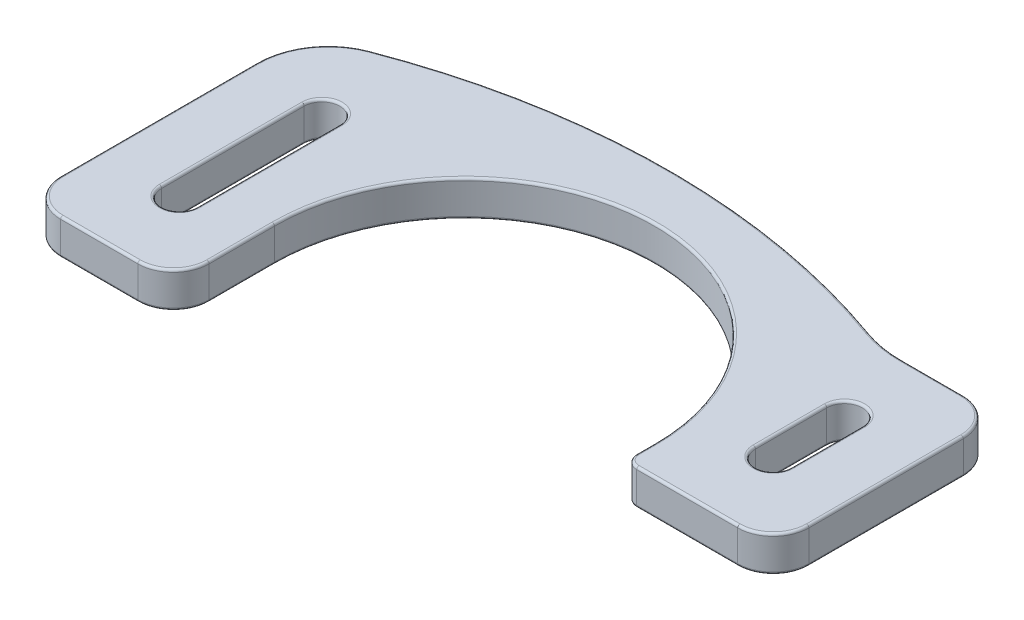
SolidWorks part; units mm, degrees
ref_plane "Front Plane" through (0, 0, 0) normal (0, 0, 1) x (1, 0, 0)
ref_plane "Top Plane" through (0, 0, 0) normal (0, 1, 0) x (1, 0, 0)
ref_plane "Right Plane" through (0, 0, 0) normal (1, 0, 0) x (0, 0, -1)
sketch "Sketch1" plane through (0, 0, 0) normal (0, 1, 0) x (1, 0, 0)
  line L0 (22, 10) -> (22, 4) construction
  line L1 (23.5, 10) -> (23.5, 4)
  line L2 (20.5, 10) -> (20.5, 4)
  line L3 (-22, 10) -> (-22, -2) construction
  line L4 (-20.5, 10) -> (-20.5, -2)
  line L5 (-23.5, 10) -> (-23.5, -2)
  line L6 (28.5, 13.5) -> (28.5, 0.5)
  line L7 (-28.5, 11.0249) -> (-28.5, -5.5)
  line L8 (-25.5, -8.5) -> (-19, -8.5)
  line L9 (25.5, -2.5) -> (17, -2.5)
  line L10 (20.3007, 16.5) -> (25.5, 16.5)
  line L11 (-16, 0) -> (-16, -5.5)
  line L12 (16, 0) -> (16, -1.5)
  arc A0 (16, 0) -> (-16, 0) centre (0, 0) ccw
  arc A1 (23.5, 10) -> (20.5, 10) centre (22, 10) ccw
  arc A2 (20.5, 4) -> (23.5, 4) centre (22, 4) ccw
  arc A3 (-20.5, 10) -> (-23.5, 10) centre (-22, 10) ccw
  arc A4 (-23.5, -2) -> (-20.5, -2) centre (-22, -2) ccw
  arc A5 (16.9379, 17.0824) -> (-24.6401, 16.6303) centre (-3.2392, -39.4232) ccw
  arc A6 (-28.5, 11.0249) -> (-24.6401, 16.6303) centre (-22.5, 11.0249) cw
  arc A7 (-19, -8.5) -> (-16, -5.5) centre (-19, -5.5) ccw
  arc A8 (-28.5, -5.5) -> (-25.5, -8.5) centre (-25.5, -5.5) ccw
  arc A9 (28.5, 13.5) -> (25.5, 16.5) centre (25.5, 13.5) ccw
  arc A10 (28.5, 0.5) -> (25.5, -2.5) centre (25.5, 0.5) cw
  arc A11 (20.3007, 16.5) -> (16.9379, 17.0824) centre (20.3007, 26.5) cw
  arc A12 (17, -2.5) -> (16, -1.5) centre (17, -1.5) cw
  point P5 (22, 7)
  point P12 (-22, 4)
  point P28 (-28.5, 15)
  point P35 (28.5, 16.5)
  point P40 (18.5, 16.5)
  dimension "D1" = 32
  dimension "D15" = 10
  dimension "D16" = 60
  dimension "D17" = 6
  dimension "D18" = 3
  dimension "D19" = 3
  dimension "D20" = 10
  dimension "D21" = 1
  dimension "D2" = 3
  dimension "D3" = 3
  dimension "D4" = 5
  dimension "D5" = 22
  dimension "D6" = 22
  dimension "D7" = 6
  dimension "D8" = 12
  dimension "D9" = 10
  dimension "D10" = 5
  dimension "D11" = 6.5
  dimension "D12" = 6.5
  dimension "D13" = 6.5
  dimension "D14" = 5
extrude "Boss-Extrude1" add sketch "Sketch1" along normal blind 3
fillet "Fillet2" radius 0.2 48 edges at (-22, 0, 3.5) (-23.5, 0, -4) (-22, 0, -11.5) (-20.5, 0, -4) (22, 0, -2.5) (20.5, 0, -7) (22, 0, -11.5) (23.5, 0, -7) (-28.5, 0, -2.7625) (-27.6213, 0, 7.6213) (-22.25, 0, 8.5) (-16.8787, 0, 7.6213) (-16, 0, 2.75) (0, 0, -16) (16, 0, 0.75) (16.2929, 0, 2.2071) (21.25, 0, 2.5) (27.6213, 0, 1.6213) (28.5, 0, -7) (27.6213, 0, -15.6213) (22.9004, 0, -16.5) (18.5943, 0, -16.6467) (-3.8915, 0, -20.5732) (-27.4417, 0, -14.4278) (-23.5, 3, -4) (-22, 3, 3.5) (-20.5, 3, -4) (-22, 3, -11.5) (-3.8915, 3, -20.5732) (18.5943, 3, -16.6467) (22.9004, 3, -16.5) (27.6213, 3, -15.6213) (28.5, 3, -7) (27.6213, 3, 1.6213) (21.25, 3, 2.5) (16.2929, 3, 2.2071) (16, 3, 0.75) (0, 3, -16) (-16, 3, 2.75) (-16.8787, 3, 7.6213) (-22.25, 3, 8.5) (-27.6213, 3, 7.6213) (-28.5, 3, -2.7625) (-27.4417, 3, -14.4278) (20.5, 3, -7) (22, 3, -2.5) (23.5, 3, -7) (22, 3, -11.5)
